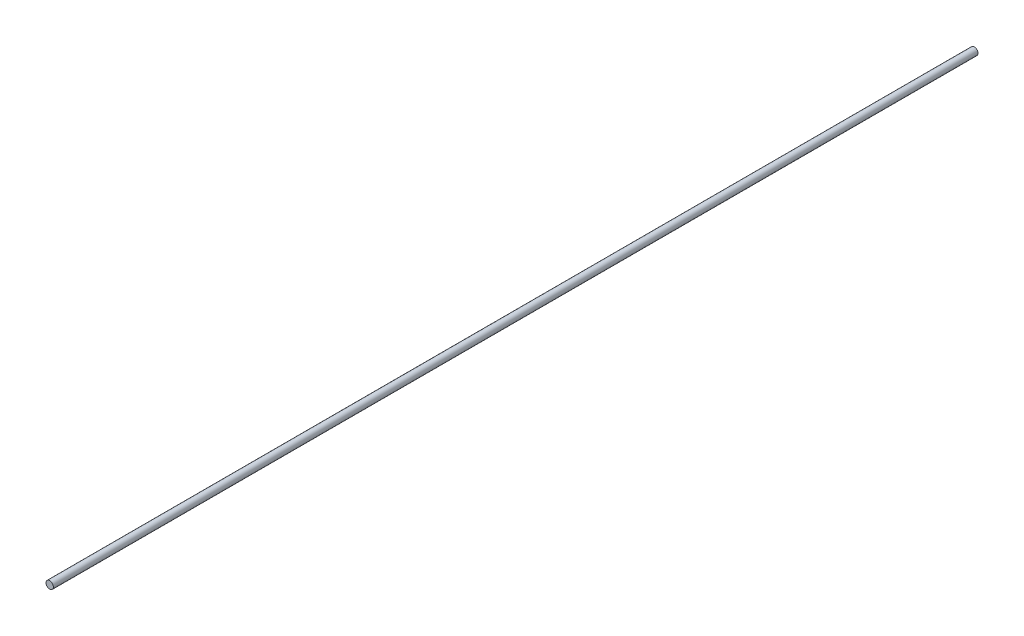
SolidWorks part; units mm, degrees
ref_plane "Front Plane" through (0, 0, 0) normal (0, 0, 1) x (1, 0, 0)
ref_plane "Top Plane" through (0, 0, 0) normal (0, 1, 0) x (1, 0, 0)
ref_plane "Right Plane" through (0, 0, 0) normal (1, 0, 0) x (0, 0, -1)
sketch "Sketch1" plane through (0, 0, 0) normal (0, 0, 1) x (1, 0, 0)
  circle A1 centre (65, 0) radius 4
extrude "Boss-Extrude1" add sketch "Sketch1" against normal blind 1000
